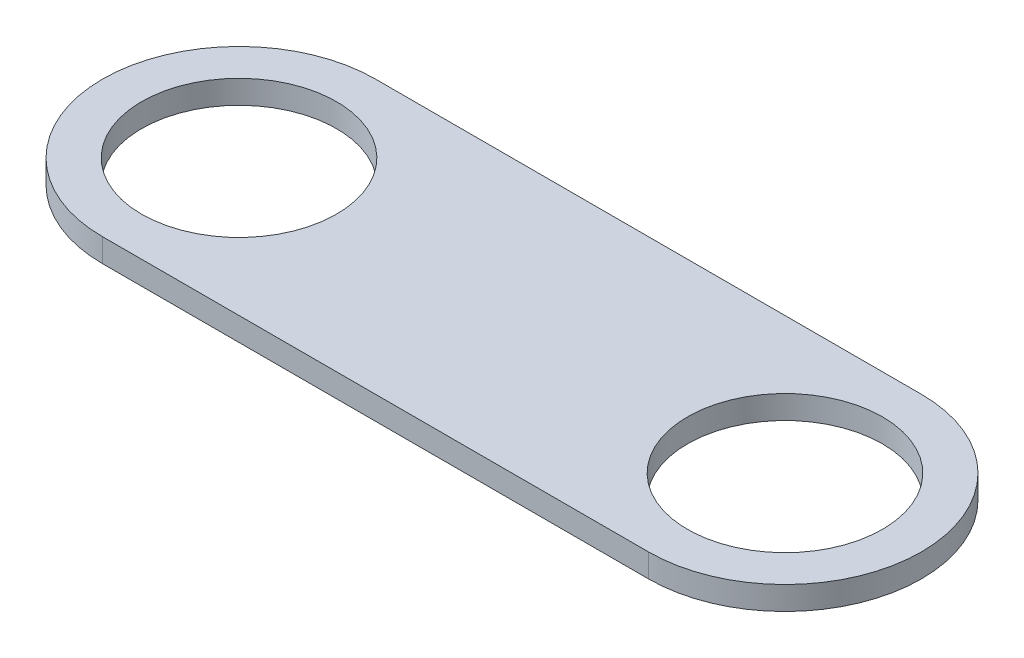
SolidWorks part; units mm, degrees
ref_plane "Front Plane" through (0, 0, 0) normal (0, 0, 1) x (1, 0, 0)
ref_plane "Top Plane" through (0, 0, 0) normal (0, 1, 0) x (1, 0, 0)
ref_plane "Right Plane" through (0, 0, 0) normal (1, 0, 0) x (0, 0, -1)
sketch "Sketch1" plane through (0, 0, 0) normal (0, 1, 0) x (1, 0, 0)
  line L0 (35, 0) -> (-35, 0)
  line L1 (-35, -35) -> (35, -35)
  arc A0 (-35, 0) -> (-35, -35) centre (-35, -17.5) ccw
  arc A1 (35, -35) -> (35, 0) centre (35, -17.5) ccw
  point P4 (0, 0)
  dimension "D1" = 70
  dimension "D2" = 35
extrude "Boss-Extrude1" add sketch "Sketch1" along normal blind 3
sketch "Sketch2" plane through (0, 3, 0) normal (0, 1, 0) x (1, 0, 0)
  line L0 (-35, 0) -> (-35, -35) construction
  line L1 (0, 0) -> (0, -35) construction
  line L2 (-35, -35) -> (35, -35) construction
  circle A0 centre (-35, -17.5) radius 12.5
  arc A1 (-35, 0) -> (-35, -35) centre (-35, -17.5) ccw construction
  circle A2 centre (35, -17.5) radius 12.5
  dimension "D1" = 5
extrude "Cut-Extrude1" cut sketch "Sketch2" against normal through all
